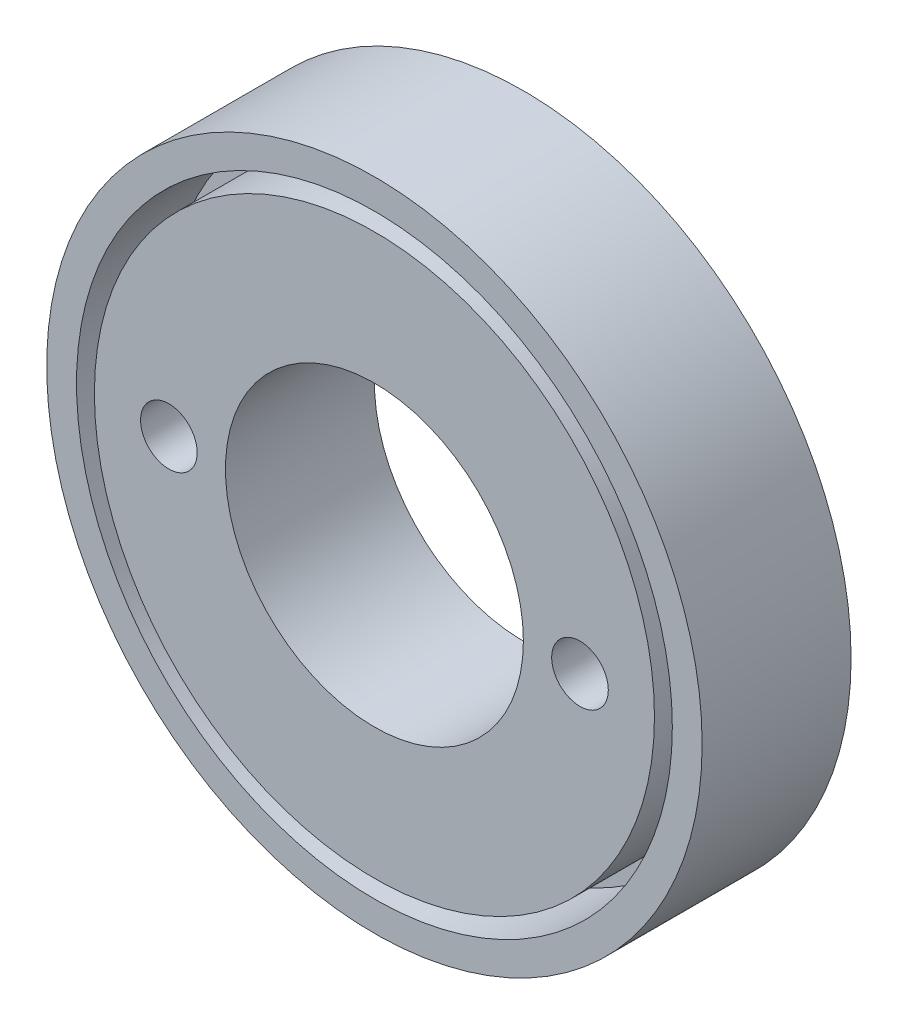
SolidWorks part; units mm, degrees
ref_plane "Front Plane" through (0, 0, 0) normal (0, 0, 1) x (1, 0, 0)
ref_plane "Top Plane" through (0, 0, 0) normal (0, 1, 0) x (1, 0, 0)
ref_plane "Right Plane" through (0, 0, 0) normal (1, 0, 0) x (0, 0, -1)
sketch "Sketch1" plane through (0, 0, 0) normal (0, 0, 1) x (1, 0, 0)
  circle A0 centre (0, 0) radius 55
  circle A1 centre (0, 0) radius 25
  dimension "D1" = 110
  dimension "D2" = 50
extrude "Boss-Extrude1" add sketch "Sketch1" along normal blind 10 and the other way blind 15
sketch "Sketch2" plane through (0, 0, 10) normal (0, 0, 1) x (1, 0, 0)
  line L0 (0, -55) -> (0, 55) construction
  circle A0 centre (0, 0) radius 50
  circle A1 centre (0, 0) radius 47
  circle A2 centre (-34.5, 0) radius 4.75
  circle A3 centre (34.5, 0) radius 4.75
  dimension "D1" = 100
  dimension "D2" = 94
  dimension "D3" = 9.5
  dimension "D4" = 34.5
extrude "Cut-Extrude1" cut sketch "Sketch2" against normal blind 15 contours A3 | A2 | A0 A1
